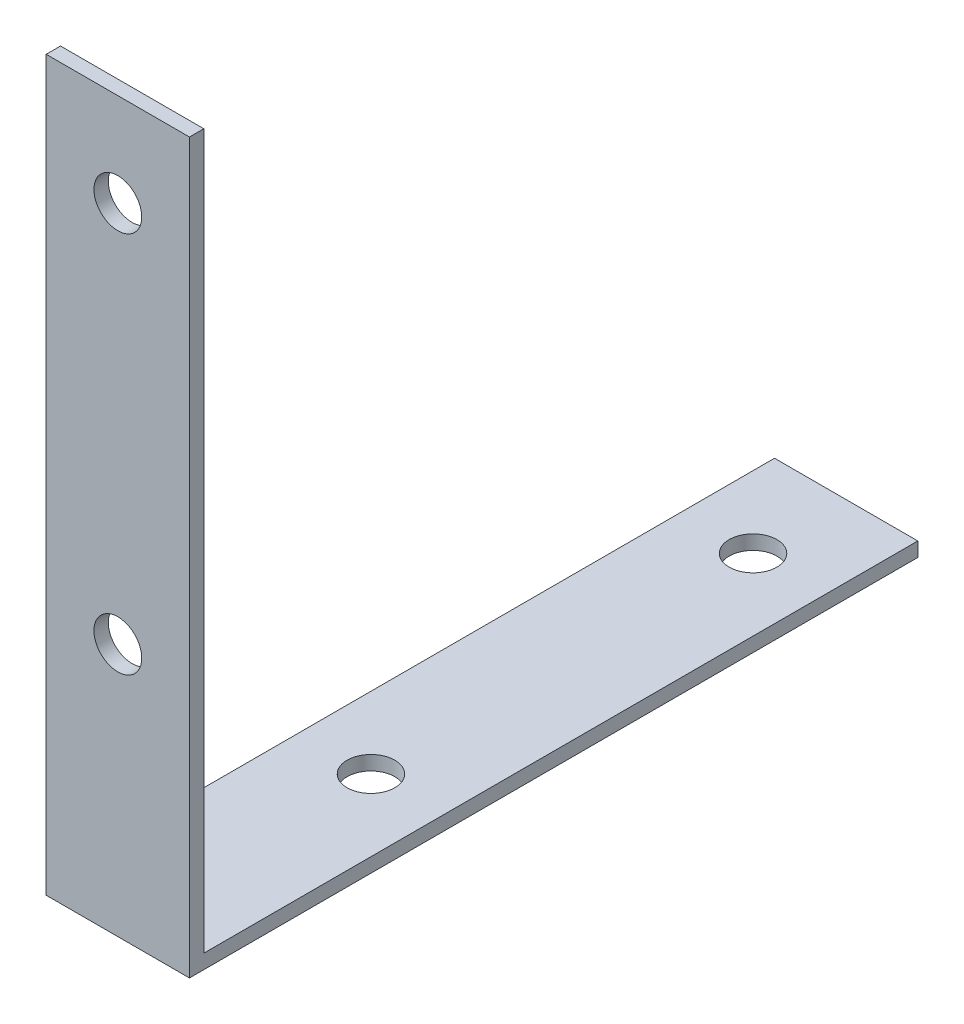
SolidWorks part; units mm, degrees
material "AISI 1020 钢，冷轧"
ref_plane "前视基准面" through (0, 0, 0) normal (0, 0, 1) x (1, 0, 0)
ref_plane "上视基准面" through (0, 0, 0) normal (0, 1, 0) x (1, 0, 0)
ref_plane "右视基准面" through (0, 0, 0) normal (1, 0, 0) x (0, 0, -1)
other "Configuration Table"
sketch "草图1" plane through (0, 0, 0) normal (1, 0, 0) x (0, 0, -1)
  line L0 (0, 0) -> (61, 0)
  line L1 (61, 0) -> (61, 1.2)
  line L2 (61, 1.2) -> (1.2, 1.2)
  line L3 (1.2, 1.2) -> (1.2, 61)
  line L4 (1.2, 61) -> (0, 61)
  line L5 (0, 61) -> (0, 0)
  dimension "D1" = 61
  dimension "D2" = 61
  dimension "D3" = 1.2
  dimension "D4" = 1.2
extrude "凸台-拉伸1" add sketch "草图1" along normal blind 12
sketch "草图2" plane through (0, 1.2, 0) normal (0, 1, 0) x (1, 0, 0)
  line L0 (12, 61) -> (0, 61) construction
  line L1 (6, 61) -> (6, 0) construction
  line L2 (12, 0) -> (0, 0) construction
  line L3 (12, 1.2) -> (0, 1.2) construction
  circle A0 centre (6, 21.2) radius 2
  circle A1 centre (6, 53.2) radius 2
  dimension "D1" = 4
  dimension "D2" = 4
  dimension "D3" = 20
  dimension "D4" = 32
extrude "切除-拉伸1" cut sketch "草图2" against normal blind 12
sketch "草图3" plane through (0, 0, -1.2) normal (0, 0, -1) x (-1, 0, 0)
  line L0 (-12, 61) -> (0, 61) construction
  line L1 (-6, 61) -> (-6, 0) construction
  line L2 (-12, 0) -> (0, 0) construction
  line L3 (-12, 1.2) -> (0, 1.2) construction
  circle A0 centre (-6, 21.2) radius 2
  circle A1 centre (-6, 53.2) radius 2
  dimension "D1" = 4
  dimension "D2" = 20
  dimension "D3" = 32
extrude "切除-拉伸2" cut sketch "草图3" against normal blind 12
